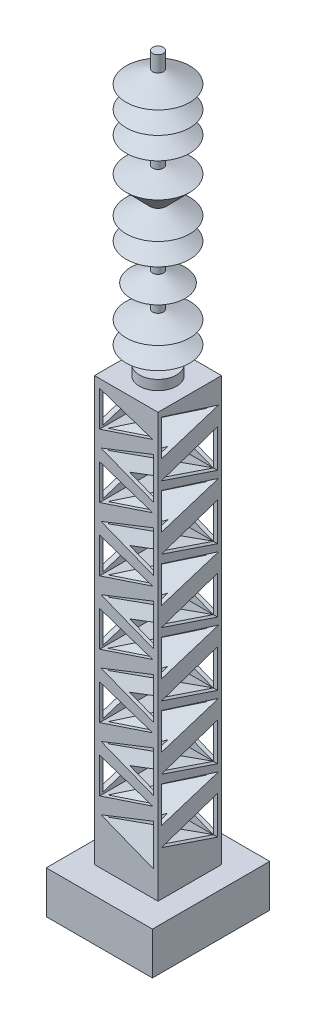
SolidWorks part; units mm, degrees
ref_plane "Alzado" through (0, 0, 0) normal (0, 0, 1) x (1, 0, 0)
ref_plane "Planta" through (0, 0, 0) normal (0, 1, 0) x (1, 0, 0)
ref_plane "Vista lateral" through (0, 0, 0) normal (1, 0, 0) x (0, 0, -1)
sketch "Croquis1" plane through (0, 0, 0) normal (0, 1, 0) x (1, 0, 0)
  line L1 (-150, 150) -> (150, 150)
  line L2 (-150, 150) -> (-150, -150)
  line L3 (-150, -150) -> (150, -150)
  line L4 (150, 150) -> (150, -150)
  line L5 (-150, 150) -> (150, -150) construction
  line L6 (-150, -150) -> (150, 150) construction
  point P0 (0, 0)
  dimension "D1" = 300
  dimension "D2" = 300
extrude "Saliente-Extruir1" add sketch "Croquis1" along normal blind 2000
sketch "Croquis2" plane through (150, 0, 0) normal (1, 0, 0) x (0, 0, -1)
  line L0 (-134.0882, 1972.1805) -> (-134.0882, 1800.9576)
  line L1 (-134.0882, 1800.9576) -> (135.9171, 1886.5691)
  line L2 (135.9171, 1886.5691) -> (-134.0882, 1972.1805)
extrude "Cortar-Extruir1" cut sketch "Croquis2" against normal blind 2000
sketch "Croquis3" plane through (150, 0, 0) normal (1, 0, 0) x (0, 0, -1)
  line L0 (131.6054, 1800.9576) -> (131.6054, 1621.5262)
  line L1 (131.6054, 1621.5262) -> (-134.0882, 1711.2419)
  line L2 (-134.0882, 1711.2419) -> (131.6054, 1800.9576)
extrude "Cortar-Extruir2" cut sketch "Croquis3" against normal blind 2000
pattern_linear "MatrizL1" count 6 spacing 300 along (0, -1, 0) of "Cortar-Extruir2", "Cortar-Extruir1"
sketch "Croquis4" plane through (0, 0, 150) normal (0, 0, 1) x (1, 0, 0)
  line L0 (-125.6863, 1959.9304) -> (-125.6863, 1792.9282)
  line L1 (-125.6863, 1792.9282) -> (124.817, 1876.4293)
  line L2 (124.817, 1876.4293) -> (-125.6863, 1959.9304)
extrude "Cortar-Extruir3" cut sketch "Croquis4" against normal blind 2000
sketch "Croquis5" plane through (0, 0, 150) normal (0, 0, 1) x (1, 0, 0)
  line L0 (129.9261, 1817.0868) -> (129.9261, 1621.1635)
  line L1 (129.9261, 1621.1635) -> (-118.9781, 1719.1573)
  line L2 (-118.9781, 1719.1573) -> (129.9261, 1817.0868)
  point P2 (-117.8192, 1692.8674)
  point P4 (120.1268, 1813.2313)
  point P5 (-118.9781, 1719.1573)
  point P6 (129.9261, 1621.1635)
extrude "Cortar-Extruir4" cut sketch "Croquis5" against normal blind 2000
pattern_linear "MatrizL2" count 6 spacing 300 along (0, -1, 0) of "Cortar-Extruir4", "Cortar-Extruir3"
ref_plane "Plano1" through (0, 0, 0) normal (0, 0, 1) x (1, 0, 0)
sketch "Croquis6" plane through (0, 0, 0) normal (0, 0, 1) x (1, 0, 0)
  line L0 (0, 2000) -> (0, 3329.9656)
  line L1 (-150, 2000) -> (150, 2000) construction
  line L2 (25.3327, 3298.7352) -> (25.3327, 3329.9656)
  line L3 (25.3327, 3329.9656) -> (0, 3329.9656)
  line L4 (25.3327, 2860.8727) -> (150, 2824.1285)
  line L5 (25.3327, 3298.7352) -> (25.3327, 3255.2813)
  line L6 (25.3327, 3255.2813) -> (150, 3192.1452)
  line L7 (150, 3192.1452) -> (25.3327, 3151.2996)
  line L8 (25.3327, 3151.2996) -> (150, 3088.1636)
  line L9 (150, 3088.1636) -> (25.3327, 3047.3179)
  line L10 (25.3327, 3047.3179) -> (150, 2984.1819)
  line L11 (150, 2984.1819) -> (25.3327, 2943.3363)
  line L12 (25.3327, 2943.3363) -> (25.3327, 2860.8727)
  line L13 (150, 2824.1285) -> (38.4443, 2710.7965)
  line L14 (25.3327, 2431.5273) -> (128.1221, 2379.471)
  line L15 (128.1221, 2379.471) -> (25.3327, 2320.3163)
  line L16 (87.6663, 2026.2907) -> (87.6663, 2046.2907)
  line L17 (38.4443, 2710.7965) -> (150, 2654.3007)
  line L18 (150, 2654.3007) -> (25.3327, 2613.4551)
  line L19 (25.3327, 2613.4551) -> (150, 2550.319)
  line L20 (150, 2550.319) -> (25.3327, 2491.0451)
  line L21 (25.3327, 2491.0451) -> (25.3327, 2431.5273)
  line L22 (87.6663, 2046.2907) -> (67.6663, 2046.2907)
  line L25 (25.3327, 2320.3163) -> (25.3327, 2272.4618)
  line L26 (25.3327, 2272.4618) -> (150, 2228.8395)
  line L27 (150, 2228.8395) -> (25.3327, 2169.5656)
  line L28 (25.3327, 2169.5656) -> (150, 2125.9433)
  line L29 (150, 2125.9433) -> (25.3327, 2066.6694)
  line L30 (25.3327, 2066.6694) -> (25.3327, 2046.2907)
  line L31 (25.3327, 2046.2907) -> (67.6663, 2046.2907)
  line L32 (87.6663, 2026.2907) -> (87.6663, 2000)
  line L33 (87.6663, 2000) -> (0, 2000)
revolve "Revolución1" add sketch "Croquis6" angle 360 about L0
sketch "Croquis7" plane through (0, 0, 0) normal (0, -1, 0) x (1, 0, 0)
  line L1 (-250.7004, -277.0446) -> (250.7004, -277.0446)
  line L2 (-250.7004, -277.0446) -> (-250.7004, 277.0446)
  line L3 (-250.7004, 277.0446) -> (250.7004, 277.0446)
  line L4 (250.7004, -277.0446) -> (250.7004, 277.0446)
  line L5 (-250.7004, -277.0446) -> (250.7004, 277.0446) construction
  line L6 (-250.7004, 277.0446) -> (250.7004, -277.0446) construction
  point P0 (0, 0)
extrude "Saliente-Extruir2" add sketch "Croquis7" along normal blind 200
